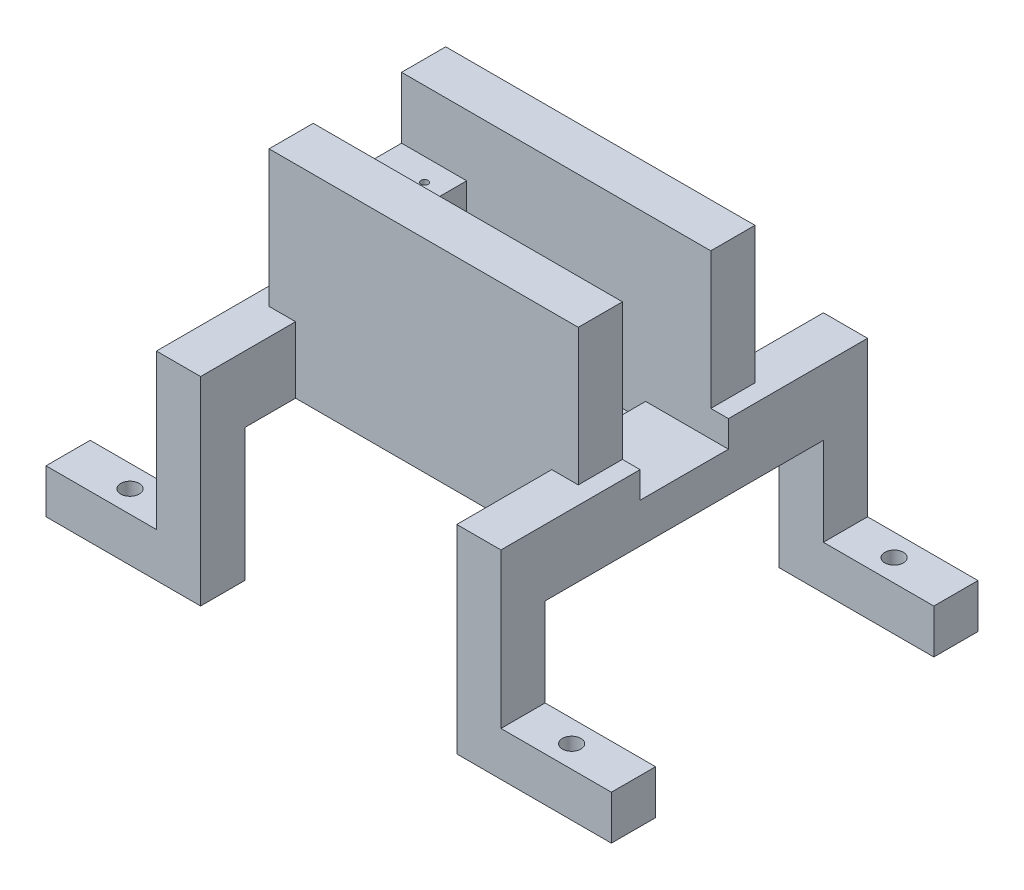
SolidWorks part; units mm, degrees
ref_plane "Front Plane" through (0, 0, 0) normal (0, 0, 1) x (1, 0, 0)
ref_plane "Top Plane" through (0, 0, 0) normal (0, 1, 0) x (1, 0, 0)
ref_plane "Right Plane" through (0, 0, 0) normal (1, 0, 0) x (0, 0, -1)
sketch "Esquisse1" plane through (0, 0, 0) normal (0, 0, 1) x (1, 0, 0)
  line L1 (-35, 25) -> (35, 25)
  line L2 (-35, 25) -> (-35, -25)
  line L3 (-35, -25) -> (35, -25)
  line L4 (35, 25) -> (35, -25)
  line L5 (-35, 25) -> (35, -25) construction
  line L6 (-35, -25) -> (35, 25) construction
  point P1 (0, 0)
  dimension "D1" = 50
  dimension "D2" = 70
extrude "Boss.-Extru.1" add sketch "Esquisse1" along normal blind 50
sketch "Esquisse2" plane through (0, 25, 0) normal (0, 1, 0) x (1, 0, 0)
  line L0 (0, 0) -> (0, -50) construction
  line L1 (-20.25, -15) -> (20.25, -15)
  line L2 (-20.25, -15) -> (-20.25, -35)
  line L3 (-20.25, -35) -> (20.25, -35)
  line L4 (20.25, -15) -> (20.25, -35)
  line L5 (-20.25, -15) -> (20.25, -35) construction
  line L6 (-20.25, -35) -> (20.25, -15) construction
  line L7 (35, 0) -> (-35, 0) construction
  line L8 (-35, -25) -> (36.4795, -25) construction
  line L9 (-35, -50) -> (-35, 0) construction
  point P0 (0, -25)
  point P14 (0, -25)
  dimension "D1" = 40.5
  dimension "D2" = 20
extrude "Enlèv. mat.-Extru.1" cut sketch "Esquisse2" against normal blind 38
sketch "Esquisse3" plane through (0, 25, 0) normal (0, 1, 0) x (1, 0, 0)
  line L0 (20.25, -20) -> (35, -20) construction
  line L1 (20.25, -25) -> (20.25, -15) construction
  line L2 (35, -50) -> (35, 0) construction
  line L3 (20.25, 0) -> (20.25, -20) construction
  line L4 (35, 0) -> (-35, 0) construction
  line L5 (20.25, -15) -> (-20.25, -15) construction
  line L6 (20.25, -15) -> (29.7525, -15)
  line L7 (20.25, -15) -> (20.25, -35)
  line L8 (20.25, -35) -> (29.7525, -35)
  line L9 (29.7525, -15) -> (29.7525, -35)
  line L10 (-20.25, -35) -> (20.25, -35) construction
  line L11 (0, 0) -> (0, -50) construction
  line L12 (35, -50) -> (-35, -50) construction
  line L13 (-20.25, -35) -> (-29.7525, -35)
  line L14 (-29.7525, -15) -> (-29.7525, -35)
  line L15 (-20.25, -15) -> (-29.7525, -15)
  line L16 (-20.25, -15) -> (-20.25, -35)
extrude "Enlèv. mat.-Extru.2" cut sketch "Esquisse3" against normal blind 11
sketch "Esquisse4" plane through (0, 25, 0) normal (0, 1, 0) x (1, 0, 0)
  circle A0 centre (0, -25.1767) radius 35
  circle A1 centre (0, -25.1767) radius 49.5
  circle A2 centre (0, -25.1767) radius 60.0765
  circle A3 centre (0, -25.1767) radius 32.622
  line M24 (35, 0) -> (-35, 0)
  line M26 (-35, -50) -> (35, -50)
  dimension "D1" = 70
  dimension "D2" = 99
extrude "Boss.-Extru.2" add sketch "Esquisse4" against normal up to surface (50 mm away) contours A2 A1 | A3 A0 M24 M26 | A3 A0 M24 | A3 A0 M26 M24 | A3 A0 M26 up to face at (0, -25, 25)
ref_plane "Plan1" through (60.0765, 0, 0) normal (1, 0, 0) x (0, 0, -1)
sketch "Esquisse5" plane through (60.0765, 0, 0) normal (1, 0, 0) x (0, 0, -1)
  line L0 (-25.1767, -25) -> (-25.1767, 44.646) construction
  line L1 (-85.2532, -25) -> (34.8998, -25) construction
  line L2 (-55.1767, 20) -> (4.8233, 20)
  line L3 (-55.1767, 20) -> (-55.1767, -20)
  line L4 (-55.1767, -20) -> (4.8233, -20)
  line L5 (4.8233, 20) -> (4.8233, -20)
  line L6 (-55.1767, 20) -> (4.8233, -20) construction
  line L7 (-55.1767, -20) -> (4.8233, 20) construction
  point P2 (-25.1767, 0)
  dimension "D1" = 5
  dimension "D2" = 60
  dimension "D3" = 5
extrude "Enlèv. mat.-Extru.3" cut sketch "Esquisse5" against normal blind 24
pattern_circular "Répétition circulaire1" count 5 over 360 about axis through (0, 0, 25.1767) along (0, 1, 0) of "Enlèv. mat.-Extru.3"
sketch "Esquisse12" plane through (0, -25, 0) normal (0, -1, 0) x (1, 0, 0)
  line L1 (-37.15, 62.3267) -> (37.15, 62.3267)
  line L2 (-37.15, 62.3267) -> (-37.15, -11.9733)
  line L3 (-37.15, -11.9733) -> (37.15, -11.9733)
  line L4 (37.15, 62.3267) -> (37.15, -11.9733)
  line L5 (-37.15, 62.3267) -> (37.15, -11.9733) construction
  line L6 (-37.15, -11.9733) -> (37.15, 62.3267) construction
  point P0 (0, 25.1767)
  dimension "D1" = 74.3
  dimension "D2" = 74.3
extrude "Boss.-Extru.7" add sketch "Esquisse12" along normal blind 28
sketch "Esquisse13" plane through (0, -53, 0) normal (0, -1, 0) x (1, 0, 0)
  line L0 (37.15, 62.3267) -> (-37.15, 62.3267) construction
  line L1 (-80, 80.3267) -> (80, 80.3267)
  line L2 (-80, 80.3267) -> (-80, 62.3267)
  line L3 (-80, 62.3267) -> (80, 62.3267)
  line L5 (0, 62.3267) -> (0, -43.4758) construction
  line L6 (-37.15, 25.1767) -> (69.1027, 25.1767) construction
  line L7 (-37.15, 62.3267) -> (-37.15, -11.9733) construction
  line L8 (-80, -11.9733) -> (80, -11.9733)
  line L10 (-80, -29.9733) -> (80, -29.9733)
  line L11 (-80, -29.9733) -> (-80, -11.9733)
  line L12 (80, 80.3267) -> (80, 62.3267)
  line L13 (80, -29.9733) -> (80, -11.9733)
  dimension "D1" = 80
  dimension "D2" = 18
extrude "Boss.-Extru.8" add sketch "Esquisse13" against normal blind 10
sketch "Esquisse15" plane through (0, -20, 0) normal (0, 1, 0) x (1, 0, 0)
  circle A0 centre (0, -25.1767) radius 60.0765
extrude "Boss.-Extru.9" add sketch "Esquisse15" against normal up to surface (5 mm away) up to face at (0, -25, 85.2532)
sketch "Esquisse16" plane through (0, -53, 0) normal (0, -1, 0) x (1, 0, 0)
  line L0 (0, 80.3267) -> (0, -47.6865) construction
  line L1 (80, 80.3267) -> (-80, 80.3267) construction
  line L2 (-37.15, 25.1767) -> (70.2195, 25.1767) construction
  line L3 (-37.15, 62.3267) -> (-37.15, -11.9733) construction
  line L5 (-26.85, 60.1767) -> (33.15, 60.1767)
  line L6 (-26.85, 60.1767) -> (-26.85, -9.8233)
  line L7 (-26.85, -9.8233) -> (33.15, -9.8233)
  line L8 (33.15, 60.1767) -> (33.15, -9.8233)
  line L9 (-26.85, 60.1767) -> (33.15, -9.8233) construction
  line L10 (-26.85, -9.8233) -> (33.15, 60.1767) construction
  line L11 (37.15, -11.9733) -> (37.15, 62.3267) construction
  point P10 (3.15, 25.1767)
  dimension "D1" = 70
  dimension "D2" = 60
  dimension "D3" = 4
extrude "Enlèv. mat.-Extru.4" cut sketch "Esquisse16" against normal blind 28
sketch "Esquisse17" plane through (37.15, 0, 0) normal (1, 0, 0) x (0, 0, -1)
  line L0 (-25.1767, -53) -> (-25.1767, -7.7059) construction
  line L1 (11.9733, -53) -> (-62.3267, -53) construction
  line L2 (11.9733, -25) -> (-62.3267, -25) construction
  line L3 (-55.3267, -25) -> (4.9733, -25)
  line L4 (-55.3267, -25) -> (-55.3267, -53)
  line L5 (-55.3267, -53) -> (4.9733, -53)
  line L6 (4.9733, -25) -> (4.9733, -53)
  line L7 (-62.3267, -43) -> (-62.3267, -25) construction
  line L8 (11.9733, -43) -> (11.9733, -25) construction
  dimension "D1" = 7
  dimension "D2" = 7
extrude "Enlèv. mat.-Extru.5" cut sketch "Esquisse17" against normal up to surface (74.3 mm away) up to face at (-37.15, -40.3333, 25.1767)
sketch "Esquisse18" plane through (0, 0, 62.3267) normal (0, 0, 1) x (1, 0, 0)
  line L0 (0, -43) -> (0, 44.9434) construction
  line L1 (80, -43) -> (-80, -43) construction
  line L2 (-37.15, -43) -> (37.15, -43) construction
  line L3 (-27.15, -27.4892) -> (27.15, -27.4892)
  line L4 (-27.15, -27.4892) -> (-27.15, -43)
  line L5 (-27.15, -43) -> (27.15, -43)
  line L6 (27.15, -27.4892) -> (27.15, -43)
  line L7 (-37.15, -43) -> (-37.15, -25) construction
  line L8 (37.15, -43) -> (37.15, -25) construction
  dimension "D1" = 10
  dimension "D2" = 10
extrude "Enlèv. mat.-Extru.6" cut sketch "Esquisse18" against normal up to surface (74.3 mm away) up to face at (0, -34, -11.9733)
sketch "Esquisse20" plane through (0, -53, 0) normal (0, -1, 0) x (1, 0, 0)
  line L0 (-60.0765, 25.1767) -> (92.0678, 25.1767) construction
  line L1 (0, 85.2532) -> (0, -47.2496) construction
  line L2 (37.15, -11.9733) -> (37.15, -4.9733) construction
  line L3 (80, -11.9733) -> (37.15, -11.9733) construction
  line L4 (-37.15, -11.9733) -> (-80, -11.9733) construction
  circle A0 centre (0, 25.1767) radius 60.0765 construction
  point P0 (67.15, -18.9733)
  point P13 (67.15, 69.3267)
  point P18 (-57.85, -18.9733)
  point P19 (-57.85, 69.3267)
  dimension "D1" = 30
  dimension "D2" = 7
  dimension "D3" = 7
  dimension "D4" = 95
hole_wizard "Trou taraudé M5x0.82" positions "Esquisse3D2" profile "Esquisse22" tap size "M5x0.8" standard "Ansi Metric"
sketch3d "Esquisse3D2"
  point P0 (-57.9319, -53, -18.9992)
  point P2 (-57.8442, -53, 69.385)
sketch "Esquisse22" plane through (-57.9319, -53, -18.9992) normal (1, 0, 0) x (0, 0, -1)
  line L0 (0, 0) -> (0, 56.1888)
  line L1 (0, 56.1888) -> (2.1, 54.927)
  line L2 (2.1, 54.927) -> (2.1, 0)
  line L5 (2.1, 0) -> (0, 0)
  line L10 (0, 56.1888) -> (-2.1, 54.927) construction
  line L11 (0, -6.35) -> (0, 107.95) construction
  dimension "Diamètre du trou pour taraudage" = 4.2
  dimension "Profondeur du trou pour taraudage" = 54.927
  dimension "Angle de pointe" = 118
cosmetic thread "Filetage de perçage5" parameters "D1"=50.927, "D2"=5
cosmetic thread "Filetage de perçage6" parameters "D1"=50.927, "D2"=5
hole_wizard "Trou taraudé M5x0.83" positions "Esquisse3D3" profile "Esquisse23" tap size "M5x0.8" standard "Ansi Metric"
sketch3d "Esquisse3D3"
  point P0 (67.1217, -53, 69.3768)
  point P2 (67.1712, -53, -19.0075)
sketch "Esquisse23" plane through (67.1217, -53, 69.3768) normal (1, 0, 0) x (0, 0, -1)
  line L0 (0, 0) -> (0, 56.1888)
  line L1 (0, 56.1888) -> (2.1, 54.927)
  line L2 (2.1, 54.927) -> (2.1, 0)
  line L5 (2.1, 0) -> (0, 0)
  line L10 (0, 56.1888) -> (-2.1, 54.927) construction
  line L11 (0, -6.35) -> (0, 107.95) construction
  dimension "Diamètre du trou pour taraudage" = 4.2
  dimension "Profondeur du trou pour taraudage" = 54.927
  dimension "Angle de pointe" = 118
cosmetic thread "Filetage de perçage7" parameters "D1"=50.927, "D2"=5
cosmetic thread "Filetage de perçage8" parameters "D1"=50.927, "D2"=5
fillet "Congé1" radius 10 4 edges at (-32.15, -43, 62.3267) (32.15, -43, 62.3267) (-32.15, -43, -11.9733) (32.15, -43, -11.9733)
sketch "Esquisse25" plane through (0, 25, 0) normal (0, 1, 0) x (1, 0, 0)
  line L0 (35, -50) -> (35, 0) construction
  line L1 (35, -15) -> (18.5293, -15)
  line L2 (35, -15) -> (35, -35)
  line L3 (35, -35) -> (18.5293, -35)
  line L4 (18.5293, -15) -> (18.5293, -35)
  line L5 (20.25, -15) -> (-20.25, -15) construction
  line L6 (-29.7525, -35) -> (29.7525, -35) construction
extrude "Enlèv. mat.-Extru.7" cut sketch "Esquisse25" against normal offset from surface (34 mm away) 4 up to face at (0, -13, 25)
sketch "Esquisse26" plane through (0, 14, 0) normal (0, 1, 0) x (1, 0, 0)
  line L0 (-20.25, -25) -> (66.628, -25) construction
  line L1 (-20.25, -35) -> (-20.25, -15) construction
  line L2 (-24.71, -25) -> (0, -25) construction
  line L3 (0, 0) -> (0, -89.8149) construction
  line L4 (-24.71, -20.075) -> (-24.71, -25) construction
  line L5 (-20.25, -15) -> (-20.25, -35) construction
  point P10 (-24.71, -29.925)
  point P12 (-24.71, -20.075)
  point P13 (20.25, -15)
  point P14 (-20.25, -15)
  dimension "D1" = 24.71
  dimension "D2" = 4.925
  dimension "D3" = 40.5
  dimension "D4" = 4.46
hole_wizard "Trou taraudé M2x0.41" positions "Esquisse3D4" profile "Esquisse27" tap size "M2x0.4" standard "Ansi Metric"
sketch3d "Esquisse3D4"
  point P0 (-24.71, 14, 20.075)
  point P3 (-24.71, 14, 29.925)
sketch "Esquisse27" plane through (-24.71, 14, 20.075) normal (1, 0, 0) x (0, 0, 1)
  line L0 (0, 0) -> (0, 15.4807)
  line L1 (0, 15.4807) -> (0.8, 15)
  line L2 (0.8, 15) -> (0.8, 0)
  line L5 (0.8, 0) -> (0, 0)
  line L10 (0, 15.4807) -> (-0.8, 15) construction
  line L11 (0, -6.35) -> (0, 107.95) construction
  dimension "Diamètre du trou pour taraudage" = 1.6
  dimension "Profondeur du trou pour taraudage" = 15
  dimension "Angle de pointe" = 118
cosmetic thread "Filetage de perçage9" parameters "D1"=4, "D2"=2
cosmetic thread "Filetage de perçage10" parameters "D1"=4, "D2"=2
sketch "Esquisse28" plane through (0, 25, 0) normal (0, 1, 0) x (1, 0, 0)
  line L1 (-35, 0) -> (35, 0)
  line L2 (-35, 0) -> (-35, -50)
  line L3 (-35, -50) -> (35, -50)
  line L4 (35, 0) -> (35, -50)
  line L5 (-93.0675, 35.6751) -> (90.3302, 35.6751)
  line L6 (-93.0675, 35.6751) -> (-93.0675, -87.9235)
  line L7 (-93.0675, -87.9235) -> (90.3302, -87.9235)
  line L8 (90.3302, 35.6751) -> (90.3302, -87.9235)
  dimension "D1" = 70
extrude "Enlèv. mat.-Extru.9" cut sketch "Esquisse28" against normal up to surface (78 mm away) up to face at (67.1712, -53, -21.1075)
sketch "Esquisse29" plane through (0, -25, 0) normal (0, -1, 0) x (1, 0, 0)
  line L1 (-38.5798, 52.4149) -> (38.2482, 52.4149)
  line L2 (-38.5798, 52.4149) -> (-38.5798, -3.7414)
  line L3 (-38.5798, -3.7414) -> (38.2482, -3.7414)
  line L4 (38.2482, 52.4149) -> (38.2482, -3.7414)
extrude "Enlèv. mat.-Extru.10" cut sketch "Esquisse29" against normal blind 7
sketch "Esquisse30" plane through (0, 25, 0) normal (0, 1, 0) x (1, 0, 0)
  line L0 (-35, -25) -> (35, -25) construction
  line L1 (-35, -5) -> (35, -5)
  line L2 (-35, -5) -> (-35, -45)
  line L3 (-35, -45) -> (35, -45)
  line L4 (35, -5) -> (35, -45)
  line L5 (-35, -50) -> (-35, 0) construction
  line L6 (35, -15) -> (35, -35) construction
  line L7 (35, -15) -> (-29.7525, -15) construction
  line L9 (35, -15) -> (35, 0) construction
  line L10 (-29.7525, -15) -> (-29.7525, -35) construction
  line L12 (-51.0826, -57.9535) -> (45.6113, -57.9535)
  line L13 (-51.0826, -57.9535) -> (-51.0826, 4.0766)
  line L14 (-51.0826, 4.0766) -> (45.6113, 4.0766)
  line L15 (45.6113, -57.9535) -> (45.6113, 4.0766)
  dimension "D1" = 10
  dimension "D2" = 40
  dimension "D3" = 5.2475
extrude "Enlèv. mat.-Extru.12" cut sketch "Esquisse30" against normal up to surface (43 mm away) up to face at (0, -18, 25)
sketch "Esquisse32" plane through (0, -18, 0) normal (0, -1, 0) x (1, 0, 0)
  line L0 (-35, 25) -> (36.2953, 25) construction
  line L1 (-35, 45) -> (-35, 5) construction
  line L2 (0, 45) -> (0, -2.9123) construction
  line L3 (-35, 45) -> (35, 45) construction
  line L4 (-35, -16.5) -> (-25, -16.5) construction
  line L9 (-50, 61.5) -> (50, 61.5) construction
  line L10 (-50, 61.5) -> (-50, -11.5) construction
  line L11 (-50, -11.5) -> (50, -11.5) construction
  line L12 (50, 61.5) -> (50, -11.5) construction
  line L13 (-50, 61.5) -> (50, -11.5) construction
  line L14 (-50, -11.5) -> (50, 61.5) construction
  line L23 (-35, 45) -> (-25, 45) construction
  line L24 (-35, 45) -> (-35, 66.5) construction
  line L25 (-35, 66.5) -> (-25, 66.5) construction
  line L26 (-25, 45) -> (-25, 66.5) construction
  line L27 (-25, 5) -> (-25, -16.5) construction
  line L28 (-35, 5) -> (-25, 5) construction
  line L29 (-35, 5) -> (-35, -16.5) construction
  line L30 (35, 5) -> (35, -16.5) construction
  line L31 (35, 5) -> (25, 5) construction
  line L32 (25, 5) -> (25, -16.5) construction
  line L33 (35, -16.5) -> (25, -16.5) construction
  line L34 (35, 66.5) -> (25, 66.5) construction
  line L35 (25, 45) -> (25, 66.5) construction
  line L36 (35, 45) -> (25, 45) construction
  line L37 (35, 45) -> (35, 66.5) construction
  line L39 (-61.8982, 66.5) -> (57.9648, 66.5) construction
  line L40 (-61.8982, 66.5) -> (-61.8982, 56.5) construction
  line L41 (-61.8982, 56.5) -> (57.9648, 56.5) construction
  line L42 (57.9648, 66.5) -> (57.9648, 56.5) construction
  line L43 (-39, 66.5) -> (-29, 66.5)
  line L44 (-39, 66.5) -> (-39, 45)
  line L46 (-29, 66.5) -> (-29, 45)
  line L47 (29, 66.5) -> (29, 45)
  line L48 (39, 66.5) -> (29, 66.5)
  line L49 (39, 66.5) -> (39, 45)
  line L50 (-39, 45) -> (-35, 39.8798)
  line L51 (39, 45) -> (35, 39.8798)
  line L52 (39, -16.5) -> (39, 5)
  line L53 (39, -16.5) -> (29, -16.5)
  line L54 (29, -16.5) -> (29, 5)
  line L55 (39, 5) -> (35, 10.1202)
  line L56 (-39, 5) -> (-35, 10.1202)
  line L57 (-39, -16.5) -> (-39, 5)
  line L58 (-39, -16.5) -> (-29, -16.5)
  line L59 (-29, -16.5) -> (-29, 5)
  arc A0 (-35, 39.8798) -> (-29, 45) centre (-91.1505, 111.7548) ccw
  arc A1 (35, 39.8798) -> (29, 45) centre (91.1505, 111.7548) cw
  arc A2 (35, 10.1202) -> (29, 5) centre (91.1505, -61.7548) ccw
  arc A3 (-35, 10.1202) -> (-29, 5) centre (-91.1505, -61.7548) cw
  point P9 (0, 25)
  line M26 (-35, 5) -> (35, 5)
  line M28 (35, 45) -> (-35, 45)
  dimension "D1" = 100
  dimension "D2" = 73
  dimension "D4" = 10
  dimension "D5" = 10
  dimension "D3" = 10
  dimension "D6" = 50
  dimension "D7" = 58
extrude "Boss.-Extru.10" add sketch "Esquisse32" against normal blind 15 contours L37 L34 L35 M28 | L26 L25 L24 M28 | L33 L30 L32 M26 | L29 L4 L27 M26
sketch "Esquisse35" plane through (0, -18, 0) normal (0, -1, 0) x (1, 0, 0)
  line L10 (-35, 25) -> (41.078, 25) construction
  line L11 (-39, 66.5) -> (-29, 66.5)
  line L12 (-39, 66.5) -> (-39, 56.5)
  line L13 (-39, 56.5) -> (-29, 56.5)
  line L14 (-29, 66.5) -> (-29, 56.5)
  line L15 (-35, 39.8798) -> (-35, 10.1202) construction
  line L16 (0, 45) -> (0, -3.5068) construction
  line L17 (-29, 45) -> (29, 45) construction
  line L18 (-39, -6.5) -> (-29, -6.5)
  line L19 (-29, -16.5) -> (-29, -6.5)
  line L20 (-39, -16.5) -> (-29, -16.5)
  line L21 (-39, -16.5) -> (-39, -6.5)
  line L22 (39, -16.5) -> (39, -6.5)
  line L23 (39, -16.5) -> (29, -16.5)
  line L24 (29, -16.5) -> (29, -6.5)
  line L25 (39, -6.5) -> (29, -6.5)
  line L26 (39, 56.5) -> (29, 56.5)
  line L27 (29, 66.5) -> (29, 56.5)
  line L28 (39, 66.5) -> (29, 66.5)
  line L29 (39, 66.5) -> (39, 56.5)
  dimension "D1" = 10
  dimension "D2" = 10
extrude "Boss.-Extru.12" add sketch "Esquisse35" along normal blind 30
sketch "Esquisse36" plane through (0, 0, 66.5) normal (0, 0, 1) x (1, 0, 0)
  line L1 (-39, -3) -> (-29, -3)
  line L2 (-39, -3) -> (-39, -18)
  line L3 (-39, -18) -> (-29, -18)
  line L4 (-29, -3) -> (-29, -18)
  line L5 (29, -3) -> (39, -3)
  line L6 (29, -3) -> (29, -18)
  line L7 (29, -18) -> (39, -18)
  line L8 (39, -3) -> (39, -18)
extrude "Boss.-Extru.13" add sketch "Esquisse36" against normal up to surface (83 mm away) up to face at (-34, -25.5, -16.5)
sketch "Esquisse37" plane through (0, -48, 0) normal (0, -1, 0) x (1, 0, 0)
  line L0 (-39, 25) -> (48.8519, 25) construction
  line L1 (-39, 56.5) -> (-39, -6.5) construction
  line L2 (0, 45) -> (0, -16.9312) construction
  line L3 (-29, 45) -> (29, 45) construction
  line L4 (-29, -6.5) -> (-64, -6.5)
  line L5 (-50, 61.5) -> (50, 61.5) construction
  line L6 (-50, 61.5) -> (-50, -11.5) construction
  line L7 (-50, -11.5) -> (50, -11.5) construction
  line L8 (50, 61.5) -> (50, -11.5) construction
  line L9 (-50, 61.5) -> (50, -11.5) construction
  line L10 (-50, -11.5) -> (50, 61.5) construction
  line L11 (-29, 66.5) -> (-64, 66.5)
  line L12 (-29, 66.5) -> (-29, 56.5)
  line L13 (-29, 56.5) -> (-64, 56.5)
  line L14 (-64, 66.5) -> (-64, 56.5)
  line L15 (-64, -16.5) -> (-64, -6.5)
  line L16 (-29, -16.5) -> (-64, -16.5)
  line L17 (-29, -16.5) -> (-29, -6.5)
  line L18 (29, -16.5) -> (29, -6.5)
  line L19 (29, -16.5) -> (64, -16.5)
  line L20 (64, -16.5) -> (64, -6.5)
  line L21 (29, -6.5) -> (64, -6.5)
  line L22 (29, 56.5) -> (64, 56.5)
  line L23 (64, 66.5) -> (64, 56.5)
  line L24 (29, 66.5) -> (64, 66.5)
  line L25 (29, 66.5) -> (29, 56.5)
  circle A0 centre (-50, 61.5) radius 2
  circle A1 centre (-50, -11.5) radius 2
  circle A2 centre (50, 61.5) radius 2
  circle A3 centre (50, -11.5) radius 2
  point P9 (0, 25)
  dimension "D1" = 100
  dimension "D2" = 73
  dimension "D3" = 10
  dimension "D4" = 35
extrude "Boss.-Extru.14" add sketch "Esquisse37" against normal blind 10
sketch "Esquisse38" plane through (-20.25, 0, 0) normal (1, 0, 0) x (0, 0, -1)
  line L0 (-35, 14) -> (-15, 14) construction
  line L1 (-53.47, 25.935) -> (-1.5029, 25.935)
  line L2 (-53.47, 25.935) -> (-53.47, 14)
  line L3 (-53.47, 14) -> (-1.5029, 14)
  line L4 (-1.5029, 25.935) -> (-1.5029, 14)
extrude "Enlèv. mat.-Extru.13" cut sketch "Esquisse38" against normal up to surface and the other way up to surface up to face at (-35, 11, 25) other way up to face at (35, 11, 40)
hole_wizard "Trou taraudé M5x0.84" positions "Esquisse3D5" profile "Esquisse39" tap size "M5x0.8" standard "Ansi Metric" end condition through all
sketch3d "Esquisse3D5"
  line L0 (-50, -38, -11.5) -> (-50, -48, -11.5) construction
  line L1 (50, -38, -11.5) -> (50, -48, -11.5) construction
  line L2 (50, -38, 61.5) -> (50, -48, 61.5) construction
  line L3 (-50, -38, 61.5) -> (-50, -48, 61.5) construction
  point P0 (-50, -38, -11.5)
  point P4 (50, -38, -11.5)
  point P8 (50, -38, 61.5)
  point P12 (-50, -38, 61.5)
sketch "Esquisse39" plane through (-50, -38, -11.5) normal (1, 0, 0) x (0, 0, 1)
  line L0 (0, 0) -> (0, 10)
  line L1 (0, 10) -> (2.1, 10)
  line L2 (2.1, 10) -> (2.1, 0)
  line L5 (2.1, 0) -> (0, 0)
  line L11 (0, -6.35) -> (0, 107.95) construction
  dimension "Diamètre du trou pour taraudage jusqu'au prochain" = 4.2
  dimension "Profondeur du trou pour taraudage jusqu'au prochain" = 10
cosmetic thread "Filetage de perçage11" parameters "D2"=5
cosmetic thread "Filetage de perçage12" parameters "D2"=5
cosmetic thread "Filetage de perçage13" parameters "D2"=5
cosmetic thread "Filetage de perçage14" parameters "D2"=5
sketch "Esquisse41" plane through (29, 0, 0) normal (-1, 0, 0) x (0, 0, 1)
  line L4 (35, -9) -> (35, -3)
  line L5 (35, -3) -> (15, -3)
  line L6 (15, -3) -> (15, -9)
  line L7 (15, -9) -> (35, -9)
  line L8 (35, -9) -> (35, -3)
  line L9 (35, -3) -> (15, -3)
  line L10 (15, -3) -> (15, -9)
  line L11 (15, -9) -> (35, -9)
  dimension "D1" = 0
extrude "Enlèv. mat.-Extru.14" cut sketch "Esquisse41" against normal up to surface (10 mm away) up to face at (39, -24.25, 25)
sketch "Esquisse42" plane through (0, 14, 0) normal (0, 1, 0) x (1, 0, 0)
  line L0 (35, -5) -> (35, -15) construction
  line L1 (-35, -5) -> (35, -5)
  line L2 (-35, -5) -> (-35, -15)
  line L3 (-35, -15) -> (35, -15)
  line L4 (35, -5) -> (35, -15)
  line L5 (35, -5) -> (35, -15) construction
  line L6 (-35, -25) -> (50.1773, -25) construction
  line L7 (-35, -45) -> (-35, -5) construction
  line L8 (-35, -35) -> (35, -35)
  line L9 (35, -45) -> (35, -35)
  line L10 (-35, -45) -> (35, -45)
  line L11 (-35, -45) -> (-35, -35)
extrude "Boss.-Extru.15" add sketch "Esquisse42" along normal blind 13.9
equation "\"1c\"=0.00854149"
equation "\"D7@Esquisse32\"=\"D6@Esquisse32\"+8mm"
